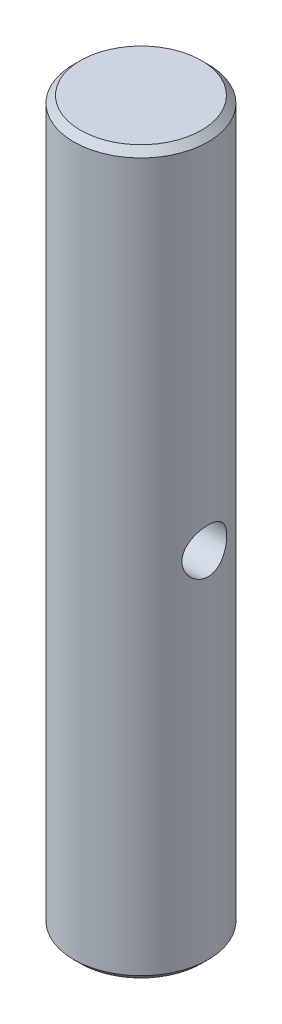
SolidWorks part; units mm, degrees
ref_plane "Front Plane" through (0, 0, 0) normal (0, 0, 1) x (1, 0, 0)
ref_plane "Top Plane" through (0, 0, 0) normal (0, 1, 0) x (1, 0, 0)
ref_plane "Right Plane" through (0, 0, 0) normal (1, 0, 0) x (0, 0, -1)
sketch "Sketch1" plane through (0, 0, 0) normal (0, 1, 0) x (1, 0, 0)
  circle A0 centre (0, 0) radius 7.495
  dimension "D1" = 14.99
extrude "Boss-Extrude1" add sketch "Sketch1" along normal blind 80.5
sketch "Sketch2" plane through (0, 0, 0) normal (1, 0, 0) x (0, 0, -1)
  circle A0 centre (0, 40.25) radius 2.5
  dimension "D1" = 5
extrude "Cut-Extrude1" cut sketch "Sketch2" against normal through all both and the other way through all
chamfer "Chamfer1" distance 0.75 angle 45 2 edges at (0, 0, 7.495) (0, 80.5, 7.495)
